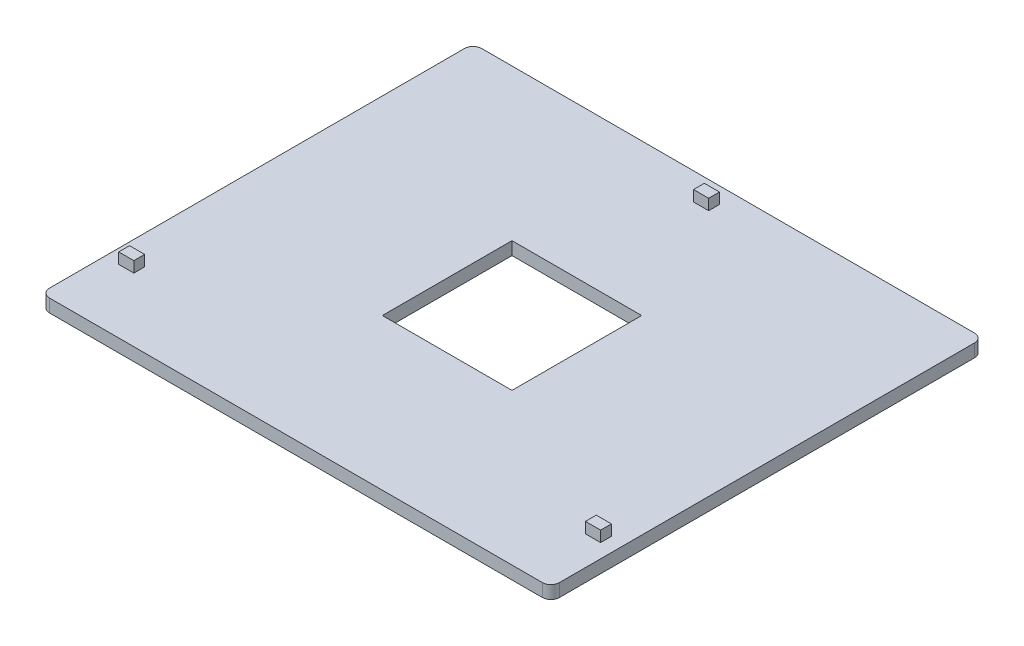
SolidWorks part; units mm, degrees
ref_plane "Front Plane" through (0, 0, 0) normal (0, 0, 1) x (1, 0, 0)
ref_plane "Top Plane" through (0, 0, 0) normal (0, 1, 0) x (1, 0, 0)
ref_plane "Right Plane" through (0, 0, 0) normal (1, 0, 0) x (0, 0, -1)
sketch "Sketch1" plane through (0, 0, 0) normal (0, 1, 0) x (1, 0, 0)
  line L1 (-59, 50) -> (59, 50)
  line L2 (-59, 50) -> (-59, -50)
  line L3 (-59, -50) -> (59, -50)
  line L4 (59, 50) -> (59, -50)
  line L5 (-59, 50) -> (59, -50) construction
  line L6 (-59, -50) -> (59, 50) construction
  line L7 (-15, 15) -> (15, 15)
  line L8 (-15, 15) -> (-15, -15)
  line L9 (-15, -15) -> (15, -15)
  line L10 (15, 15) -> (15, -15)
  line L11 (-15, 15) -> (15, -15) construction
  line L12 (-15, -15) -> (15, 15) construction
  point P0 (0, 0)
  point P6 (0, 0)
  dimension "D1" = 118
  dimension "D2" = 100
  dimension "D3" = 30
  dimension "D4" = 30
extrude "Boss-Extrude1" add sketch "Sketch1" along normal blind 3
sketch "Sketch2" plane through (0, 3, 0) normal (0, 1, 0) x (1, 0, 0)
  line L0 (-59, -34) -> (59, -34) construction
  line L1 (-59, 50) -> (-59, -50) construction
  line L2 (59, -50) -> (59, 50) construction
  line L3 (-59, -50) -> (59, -50) construction
  line L4 (0, 50) -> (0, -50) construction
  line L5 (59, 50) -> (-59, 50) construction
  line L6 (55.75, -35.25) -> (52.25, -35.25)
  line L7 (-55.75, -32.75) -> (-52.25, -32.75)
  line L8 (-55.75, -32.75) -> (-55.75, -35.25)
  line L9 (-55.75, -35.25) -> (-52.25, -35.25)
  line L10 (-52.25, -32.75) -> (-52.25, -35.25)
  line L11 (-55.75, -32.75) -> (-52.25, -35.25) construction
  line L12 (-55.75, -35.25) -> (-52.25, -32.75) construction
  line L13 (52.25, -32.75) -> (52.25, -35.25)
  line L14 (55.75, -32.75) -> (52.25, -32.75)
  line L15 (55.75, -32.75) -> (55.75, -35.25)
  line L16 (-59, 45) -> (59, 45) construction
  line L18 (-1.75, 46.25) -> (1.75, 46.25)
  line L19 (-1.75, 46.25) -> (-1.75, 43.75)
  line L20 (-1.75, 43.75) -> (1.75, 43.75)
  line L21 (1.75, 46.25) -> (1.75, 43.75)
  line L22 (-1.75, 46.25) -> (1.75, 43.75) construction
  line L23 (-1.75, 43.75) -> (1.75, 46.25) construction
  point P12 (-54, -34)
  point P23 (0, 45)
  dimension "D1" = 16
  dimension "D2" = 3.5
  dimension "D3" = 2.5
  dimension "D4" = 5
  dimension "D5" = 5
  dimension "D6" = 2.5
  dimension "D7" = 3.5
extrude "Boss-Extrude2" add sketch "Sketch2" along normal blind 2.5
fillet "Fillet1" radius 2 4 edges at (-59, 1.5, -50) (59, 1.5, -50) (59, 1.5, 50) (-59, 1.5, 50)
